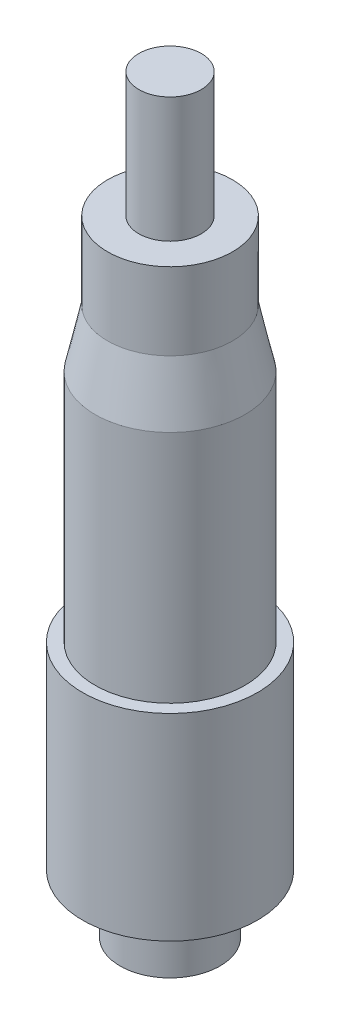
SolidWorks part; units mm, degrees
ref_plane "Front Plane" through (0, 0, 0) normal (0, 0, 1) x (1, 0, 0)
ref_plane "Top Plane" through (0, 0, 0) normal (0, 1, 0) x (1, 0, 0)
ref_plane "Right Plane" through (0, 0, 0) normal (1, 0, 0) x (0, 0, -1)
sketch "Sketch1" plane through (0, 0, 0) normal (0, 0, 1) x (1, 0, 0)
  line L0 (0, 0) -> (0, 21.8738) construction
  line L1 (0, 0) -> (29.3429, 0) construction
  line L2 (0, 60) -> (2.5, 60)
  line L3 (2.5, 60) -> (2.5, 50)
  line L4 (2.5, 50) -> (5, 50)
  line L5 (5, 50) -> (5, 43.8191)
  line L8 (6, 39.2211) -> (6, 20.4523)
  line L9 (6, 20.4523) -> (7, 20.4523)
  line L10 (7, 20.4523) -> (7, 4.6734)
  line L11 (7, 4.6734) -> (4, 4.6734)
  line L12 (4, 4.6734) -> (4, 0)
  line L13 (4, 0) -> (0, 0)
  line L14 (0, 0) -> (0, 60)
  line L15 (5, 43.8191) -> (6, 39.2211)
  dimension "D1" = 60
  dimension "D2" = 2.5
  dimension "D3" = 10
  dimension "D4" = 6
  dimension "D5" = 5
  dimension "D6" = 7
  dimension "D7" = 4
revolve "Revolve1" add sketch "Sketch1" angle 360 about L0
